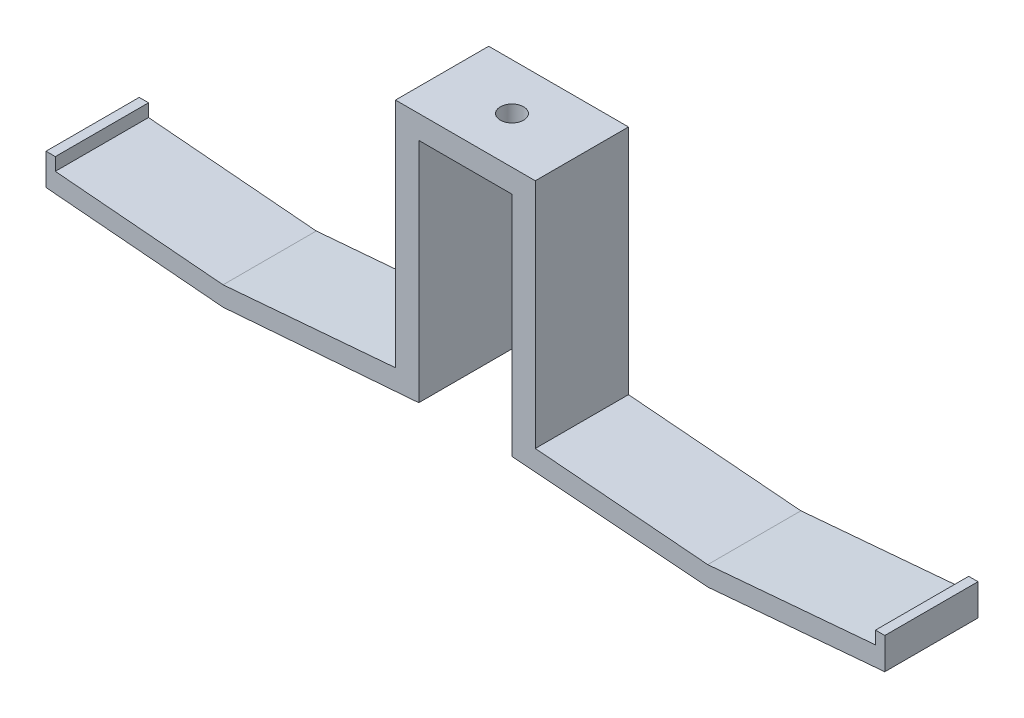
SolidWorks part; units mm, degrees
material "1345 Alloy"
ref_plane "Front Plane" through (0, 0, 0) normal (0, 0, 1) x (1, 0, 0)
ref_plane "Top Plane" through (0, 0, 0) normal (0, 1, 0) x (1, 0, 0)
ref_plane "Right Plane" through (0, 0, 0) normal (1, 0, 0) x (0, 0, -1)
sketch "Sketch2" plane through (0, 0, 0) normal (0, 0, 1) x (1, 0, 0)
  line L1 (12.7, 0) -> (12.7, -61.918)
  line L2 (12.7, -61.918) -> (66.04, -66.0514)
  line L3 (66.04, -66.0514) -> (114.3, -61.918)
  line L4 (114.3, -61.918) -> (114.3, -53.3514)
  line L5 (111.76, -53.3514) -> (111.76, -56.838)
  line L6 (111.76, -56.838) -> (66.04, -60.7538)
  line L19 (114.3, -53.3514) -> (111.76, -53.3514)
  line L20 (0, 125.2351) -> (0, -75.9356) construction
  line L21 (12.7, 0) -> (-12.7, 0)
  line L22 (0, 0) -> (0, 6.35)
  line L23 (19.05, 6.35) -> (-19.05, 6.35)
  line L24 (19.05, 6.35) -> (19.05, 0)
  line L25 (19.05, 0) -> (19.05, -56.838)
  line L26 (19.05, -56.838) -> (66.04, -60.7538)
  line L27 (-19.05, 0) -> (-19.05, -56.838)
  line L28 (-19.05, 6.35) -> (-19.05, 0)
  line L29 (-12.7, 0) -> (-12.7, -61.918)
  line L30 (-12.7, -61.918) -> (-66.04, -66.0514)
  line L31 (-66.04, -66.0514) -> (-114.3, -61.918)
  line L32 (-114.3, -61.918) -> (-114.3, -53.3514)
  line L33 (-114.3, -53.3514) -> (-111.76, -53.3514)
  line L34 (-111.76, -53.3514) -> (-111.76, -56.838)
  line L35 (-111.76, -56.838) -> (-66.04, -60.7538)
  line L36 (-19.05, -56.838) -> (-66.04, -60.7538)
  dimension "D1" = 19.05
  dimension "D2" = 12.7
  dimension "D3" = 56.838
  dimension "D4" = 3.9158
  dimension "D5" = 61.918
  dimension "D6" = 2.54
  dimension "D7" = 45.72
  dimension "D8" = 46.99
  dimension "D9" = 12.7
  dimension "D10" = 6.35
extrude "Boss-Extrude1" add sketch "Sketch2" along normal blind 25.4 contours L26 L25 L24 L23 L22 L21 L1 L2 L3 L4 L19 L5 L6 | L27 L36 L35 L34 L33 L32 L31 L30 L29 L21 L22 L23 L28
sketch "Sketch3" plane through (0, 6.35, 0) normal (0, 1, 0) x (1, 0, 0)
  line L0 (19.05, -12.7) -> (-19.05, -12.7) construction
  line L1 (19.05, -25.4) -> (19.05, 0) construction
  line L2 (-19.05, -25.4) -> (-19.05, 0) construction
  circle A0 centre (0, -12.7) radius 3.175
  dimension "D1" = 6.35
extrude "Cut-Extrude1" cut sketch "Sketch3" against normal up to next
